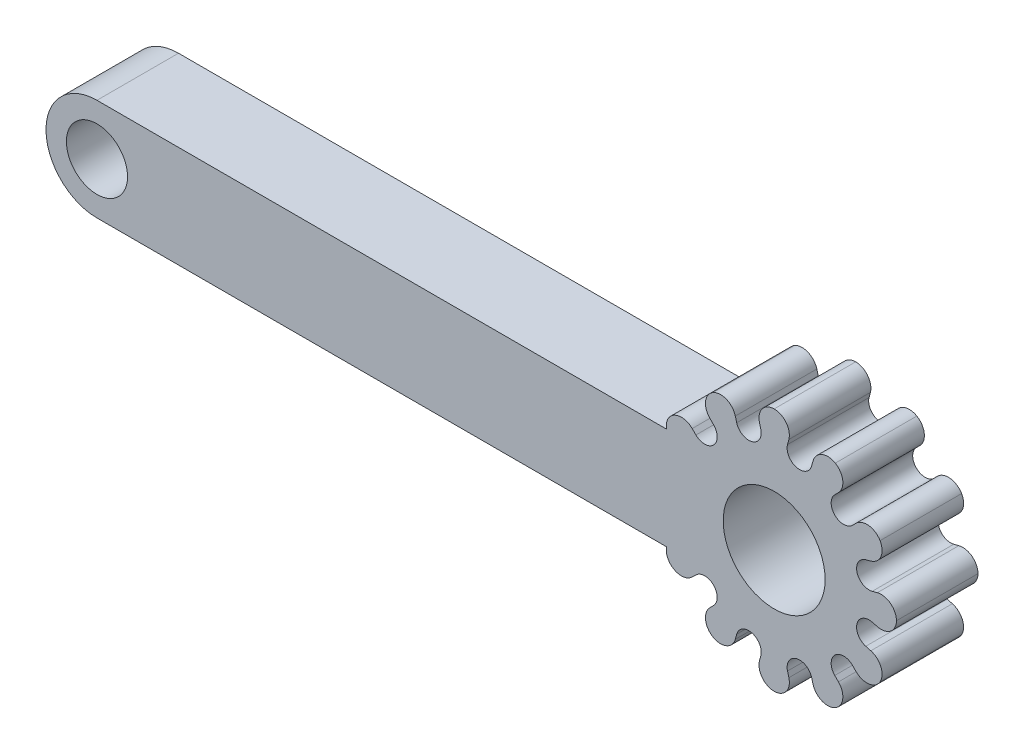
SolidWorks part; units mm, degrees
ref_plane "Front Plane" through (0, 0, 0) normal (0, 0, 1) x (1, 0, 0)
ref_plane "Top Plane" through (0, 0, 0) normal (0, 1, 0) x (1, 0, 0)
ref_plane "Right Plane" through (0, 0, 0) normal (1, 0, 0) x (0, 0, -1)
sketch "Sketch1" plane through (0, 0, 0) normal (0, 0, 1) x (1, 0, 0)
  line L0 (-18, 0) -> (15.2239, 0) construction
  line L1 (-18, 0) -> (-18, 2.5) construction
  line L2 (-18, 2.5) -> (9.7696, 2.5)
  line L3 (-18, -2.5) -> (9.7696, -2.5)
  arc A0 (-18, 2.5) -> (-18, -2.5) centre (-18, 0) ccw
  circle A1 centre (-18, 0) radius 1.5
  arc A3 (9.7696, -2.5) -> (9.7696, 2.5) centre (15.2239, 0) ccw
  point P4 (0, 0)
  dimension "D2" = 3
  dimension "D3" = 5
  dimension "D1" = 12
extrude "Boss-Extrude1" add sketch "Sketch1" along normal blind 4
sketch "Sketch2" plane through (0, 0, 4) normal (0, 0, 1) x (1, 0, 0)
  line L0 (15.2239, 0) -> (15.2239, -8.1619) construction
  line L1 (15.2239, -8.1619) -> (15.2239, 0) construction
  line L2 (15.2239, 0) -> (15.2239, 9.0593) construction
  line L3 (15.2239, 0) -> (20.1511, 8.5341) construction
  line L4 (15.2239, 0) -> (16.4715, 4.6558) construction
  line L5 (15.8789, 4.81) -> (15.9439, 5.06)
  line L6 (15.8789, 4.81) -> (17.0631, 4.4978) construction
  line L8 (17.1304, 4.7421) -> (17.0618, 4.493)
  arc A0 (15.2239, 6) -> (15.9439, 5.06) centre (15.2184, 5.25) cw
  arc A1 (9.7696, -2.5) -> (9.7696, 2.5) centre (15.2239, 0) ccw construction
  arc A2 (15.8789, 4.81) -> (17.0618, 4.493) centre (16.4715, 4.6558) ccw
  arc A3 (18.2239, 5.1962) -> (17.1304, 4.7421) centre (17.8537, 4.5439) ccw
  arc A5 (15.2239, 6) -> (18.2239, 5.1962) centre (15.8982, 2.5163) cw
  dimension "D6" = 0.75
  dimension "D1" = 30
  dimension "D2" = 0.25
  dimension "D3" = 4.82
  dimension "D4" = 0.94
  dimension "D5" = 0.72
  dimension "D8" = 15
extrude "Cut-Extrude1" cut sketch "Sketch2" against normal through all
pattern_circular "CirPattern1" count 12 over 360 about axis through (15.2239, 0, 0) along (0, 0, 1) of "Cut-Extrude1"
sketch "Sketch3" plane through (0, 0, 4) normal (0, 0, 1) x (1, 0, 0)
  line L0 (9.6651, 2.5) -> (-18, 2.5) construction
  line L1 (5.9886, 2.5) -> (17.3253, 2.5)
  line L2 (5.9886, 2.5) -> (5.9886, -2.5)
  line L3 (5.9886, -2.5) -> (17.3253, -2.5)
  line L4 (17.3253, 2.5) -> (17.3253, -2.5)
  line L5 (-18, -2.5) -> (9.6651, -2.5) construction
extrude "Boss-Extrude2" add sketch "Sketch3" against normal blind 4
sketch "Sketch4" plane through (0, 0, 4) normal (0, 0, 1) x (1, 0, 0)
  line L0 (15.2239, 6) -> (15.2239, -6) construction
  circle A0 centre (15.2239, 0) radius 2.5
  dimension "D1" = 5
extrude "Cut-Extrude2" cut sketch "Sketch4" against normal through all
